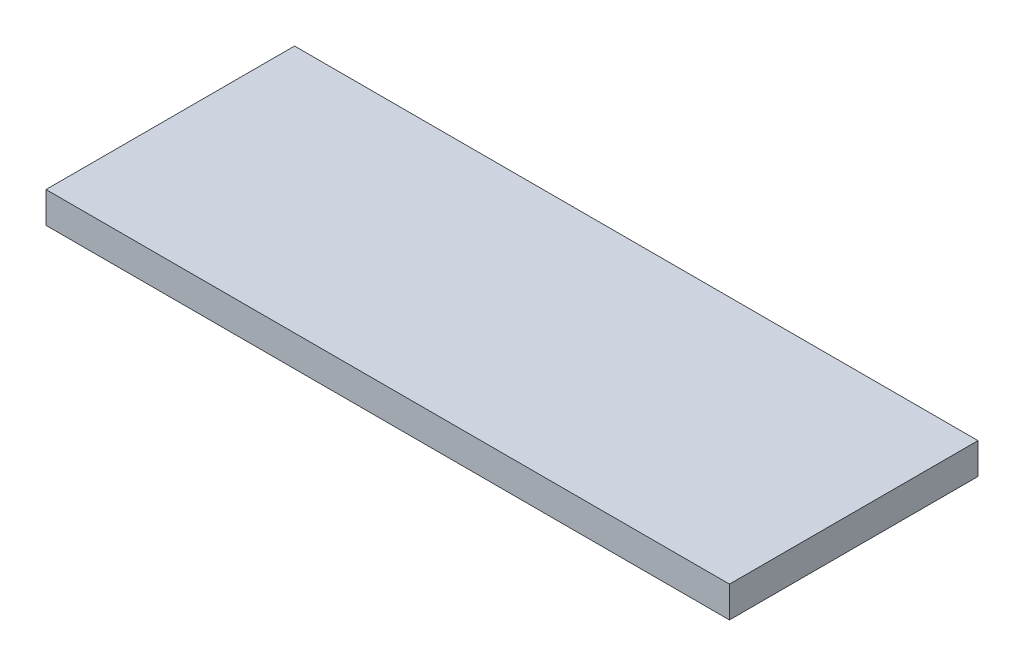
SolidWorks part; units mm, degrees
ref_plane "Front Plane" through (0, 0, 0) normal (0, 0, 1) x (1, 0, 0)
ref_plane "Top Plane" through (0, 0, 0) normal (0, 1, 0) x (1, 0, 0)
ref_plane "Right Plane" through (0, 0, 0) normal (1, 0, 0) x (0, 0, -1)
sketch "Sketch1" plane through (0, 0, 0) normal (0, 1, 0) x (1, 0, 0)
  line L1 (0, 0) -> (22, 0)
  line L2 (0, 0) -> (0, 8)
  line L3 (0, 8) -> (22, 8)
  line L4 (22, 0) -> (22, 8)
  dimension "D1" = 8
  dimension "D2" = 22
extrude "Boss-Extrude1" add sketch "Sketch1" along normal blind 1
